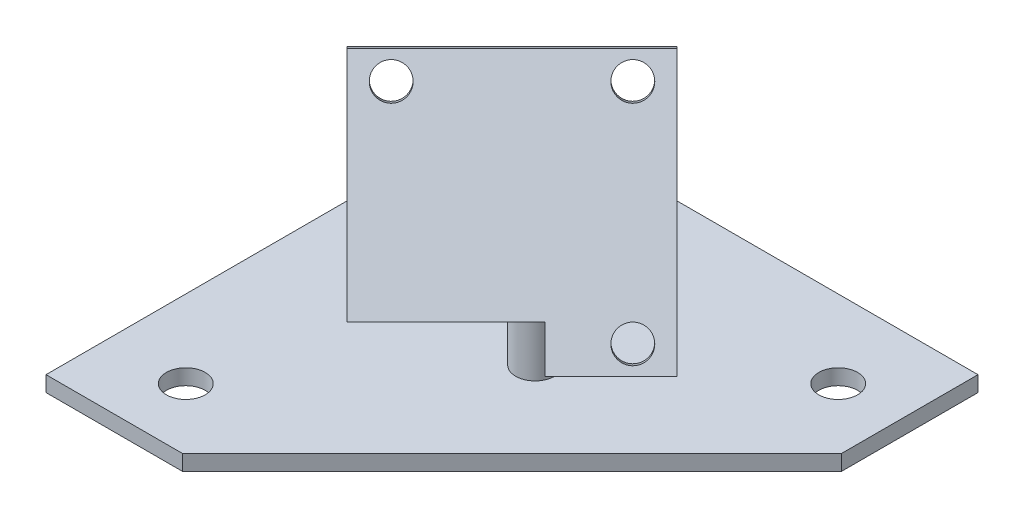
SolidWorks part; units mm, degrees
ref_plane "Front" through (0, 0, 0) normal (0, 0, 1) x (1, 0, 0)
ref_plane "Top" through (0, 0, 0) normal (0, 1, 0) x (1, 0, 0)
ref_plane "Right" through (0, 0, 0) normal (1, 0, 0) x (0, 0, -1)
sketch "草图1" plane through (0, 0, 0) normal (0, 1, 0) x (1, 0, 0)
  line L0 (90.71, 13.1364) -> (5.0331, -72.5405)
  line L1 (0, 0) -> (60, 0)
  line L2 (0, 0) -> (0, -60)
  line L3 (0, -60) -> (60, -60)
  line L4 (60, 0) -> (60, -60)
  line L5 (0, 0) -> (20, 0)
  line L6 (0, 0) -> (0, -20)
  line L7 (0, -20) -> (20, -20)
  line L8 (20, 0) -> (20, -20)
  circle A0 centre (10, -52) radius 2.5
  circle A1 centre (52, -10) radius 2.5
  dimension "D5" = 5
  dimension "D8" = 5
  dimension "D1" = 60
  dimension "D2" = 60
  dimension "D3" = 20
  dimension "D4" = 20
  dimension "D6" = 10
  dimension "D7" = 8
  dimension "D9" = 10
  dimension "D10" = 8
  dimension "D11" = 30
extrude "凸台-拉伸1" add sketch "草图1" along normal blind 2 contours L1 L8 L7 L2 L3 L4
ref_plane "基准面1" through (29.7025, 24.252, 29.7025) normal (0.6124, 0.5, 0.6124) x (-0.7071, 0, 0.7071)
sketch "草图2" plane through (29.7025, 24.252, 29.7025) normal (0.6124, 0.5, 0.6124) x (-0.7071, 0, 0.7071)
  line L0 (20.7547, -8.504) -> (-21.3736, -8.504) construction
  line L1 (-15, 18.496) -> (15, 18.496)
  line L2 (-15, 18.496) -> (-15, -11.504)
  line L3 (-15, -11.504) -> (15, -11.504)
  line L4 (15, 18.496) -> (15, -11.504)
  line L5 (-15, 18.496) -> (15, -11.504) construction
  line L6 (-15, -11.504) -> (15, 18.496) construction
  line L7 (0, -2.8326) -> (0, 36.0846) construction
  line L8 (27.4605, 3.496) -> (-33.4746, 3.496) construction
  line L10 (15, 18.496) -> (-3, 18.496)
  line L11 (15, 18.496) -> (15, 13.496)
  line L12 (15, 13.496) -> (-3, 13.496)
  line L13 (-3, 18.496) -> (-3, 13.496)
  circle A0 centre (11, -8.504) radius 2
  circle A1 centre (-11, -8.504) radius 2
  circle A2 centre (-11, 15.496) radius 2
  circle A3 centre (11, 15.496) radius 2
  point P0 (0, 3.496)
  dimension "D4" = 4
  dimension "D1" = 30
  dimension "D2" = 30
  dimension "D3" = 12
  dimension "D5" = 11
  dimension "D6" = 5
  dimension "D7" = 18
extrude "凸台-拉伸3" add sketch "草图2" along normal blind 2 separate body contours L13 L1 L2 L3 L4 L12 A2 A0 A1
sketch "草图4" plane through (0, 2, 0) normal (0, 1, 0) x (1, 0, 0)
  line L12 (36.5953, -46.4948) -> (38.3631, -48.2626)
  line L13 (23.8674, -59.2228) -> (36.5953, -46.4948)
  line L14 (0.8864, -36.2418) -> (23.8674, -59.2228)
  line L15 (36.2418, -0.8864) -> (0.8864, -36.2418)
  line L16 (60.9905, -25.6352) -> (36.2418, -0.8864)
  line L17 (38.3631, -48.2626) -> (60.9905, -25.6352)
  line L18 (36.5953, -46.4948) -> (38.3631, -48.2626)
  line L19 (23.8674, -59.2228) -> (36.5953, -46.4948)
  line L20 (0.8864, -36.2418) -> (23.8674, -59.2228)
  line L21 (36.2418, -0.8864) -> (0.8864, -36.2418)
  line L22 (60.9905, -25.6352) -> (36.2418, -0.8864)
  line L23 (38.3631, -48.2626) -> (60.9905, -25.6352)
  circle A0 centre (30.4269, -27.4459) radius 2.5
  dimension "D2" = 5
  dimension "D1" = 10
extrude "凸台-拉伸4" add sketch "草图4" along normal up to surface (21.0665 mm away) contours A0
